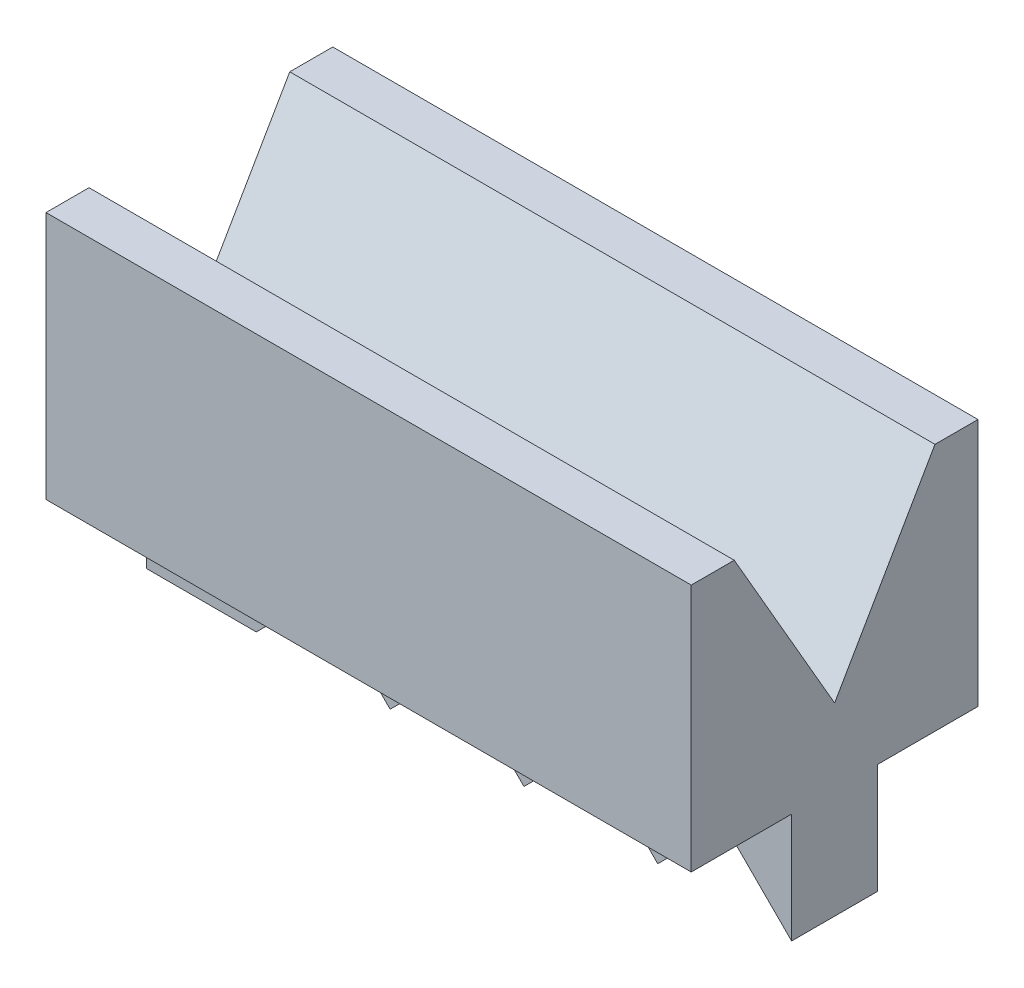
SolidWorks part; units mm, degrees
ref_plane "Front Plane" through (0, 0, 0) normal (0, 0, 1) x (1, 0, 0)
ref_plane "Top Plane" through (0, 0, 0) normal (0, 1, 0) x (1, 0, 0)
ref_plane "Right Plane" through (0, 0, 0) normal (1, 0, 0) x (0, 0, -1)
sketch "Sketch2" plane through (0, 0, 0) normal (1, 0, 0) x (0, 0, 1)
  line L0 (0, 31.3191) -> (0, -94.4468) construction
  line L1 (-9, 23) -> (9, 23)
  line L2 (9, 23) -> (9, 0)
  line L3 (9, 0) -> (30, 0)
  line L4 (30, 0) -> (30, -52)
  line L5 (30, -52) -> (21, -52)
  line L6 (21, -52) -> (0, -15.6269)
  line L7 (-21, -52) -> (0, -15.6269)
  line L8 (-30, -52) -> (-21, -52)
  line L9 (-30, 0) -> (-30, -52)
  line L10 (-9, 0) -> (-30, 0)
  line L11 (-9, 23) -> (-9, 0)
  point P9 (19.5, 0)
  point P16 (0, 23)
  dimension "D1" = 23
  dimension "D2" = 52
  dimension "D3" = 9
  dimension "D4" = 9
  dimension "D5" = 30
  dimension "D6" = 30
extrude "Boss-Extrude1" add sketch "Sketch2" along normal blind 135
sketch "Sketch3" plane through (0, 0, -9) normal (0, 0, -1) x (-1, 0, 0)
  line L0 (-135, -23) -> (-121, -9)
  line L1 (-121, -9) -> (-107, -23)
  line L2 (-135, -23) -> (0, -23) construction
  line L3 (-107, -23) -> (-93, -9)
  line L4 (-93, -9) -> (-79, -23)
  line L5 (-79, -23) -> (-65, -9)
  line L6 (-65, -9) -> (-51, -23)
  line L7 (-51, -23) -> (-37, -9)
  line L8 (-37, -9) -> (-23, -23)
  line L9 (-23, -23) -> (-135, -23)
  line M12 (-135, -23) -> (0, -23)
  dimension "D1" = 28
  dimension "D2" = 4
extrude "Cut-Extrude1" cut sketch "Sketch3" against normal up to next contours L6 L5 M12 | L4 L3 M12 | L1 L0 M12 | L8 L7 M12
